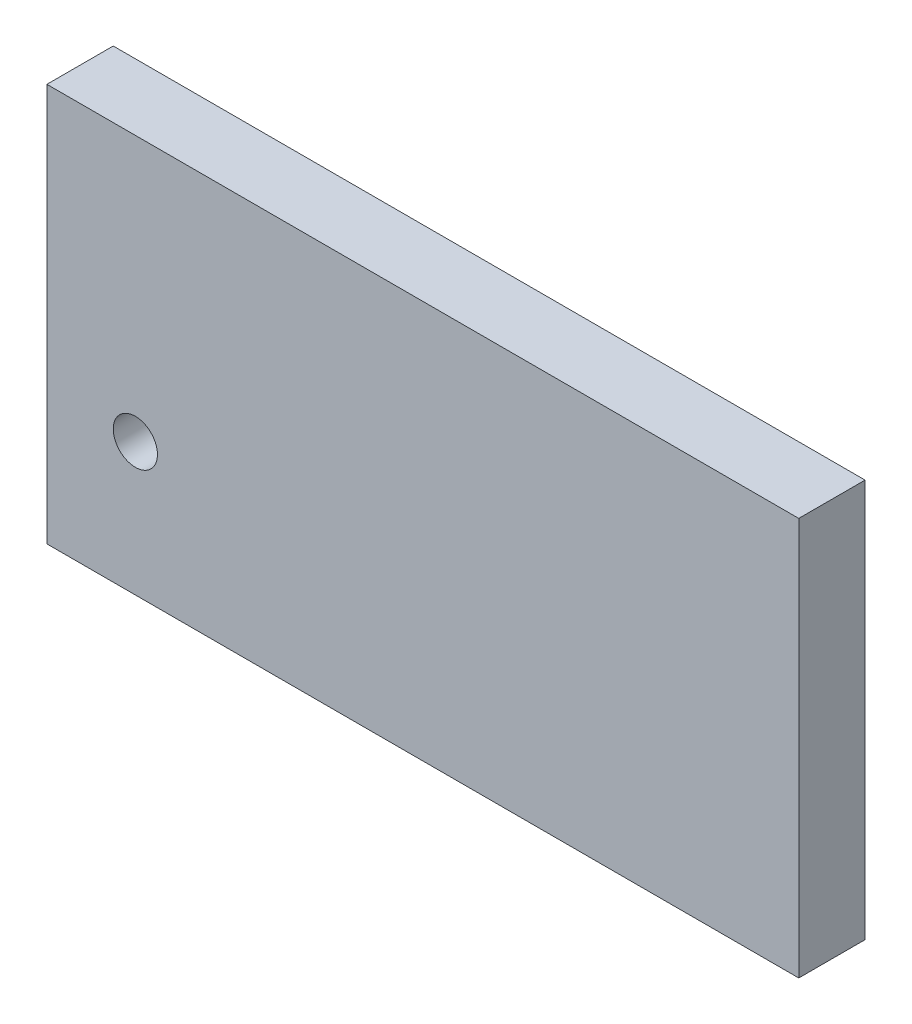
SolidWorks part; units mm, degrees
material "Pine"
ref_plane "Front Plane" through (0, 0, 0) normal (0, 0, 1) x (1, 0, 0)
ref_plane "Top Plane" through (0, 0, 0) normal (0, 1, 0) x (1, 0, 0)
ref_plane "Right Plane" through (0, 0, 0) normal (1, 0, 0) x (0, 0, -1)
sketch "Sketch2" plane through (0, 0, 0) normal (0, 0, 1) x (1, 0, 0)
  line L0 (251.8363, 27.1947) -> (467.7363, 27.1947)
  line L1 (251.8363, 141.4947) -> (467.7363, 141.4947)
  line L2 (251.8363, 141.4947) -> (251.8363, 27.1947)
  line L3 (467.7363, 141.4947) -> (467.7363, 27.1947)
  circle A0 centre (277.2363, 65.2947) radius 6.35
extrude "Boss-Extrude1" add sketch "Sketch2" along normal blind 19.05
